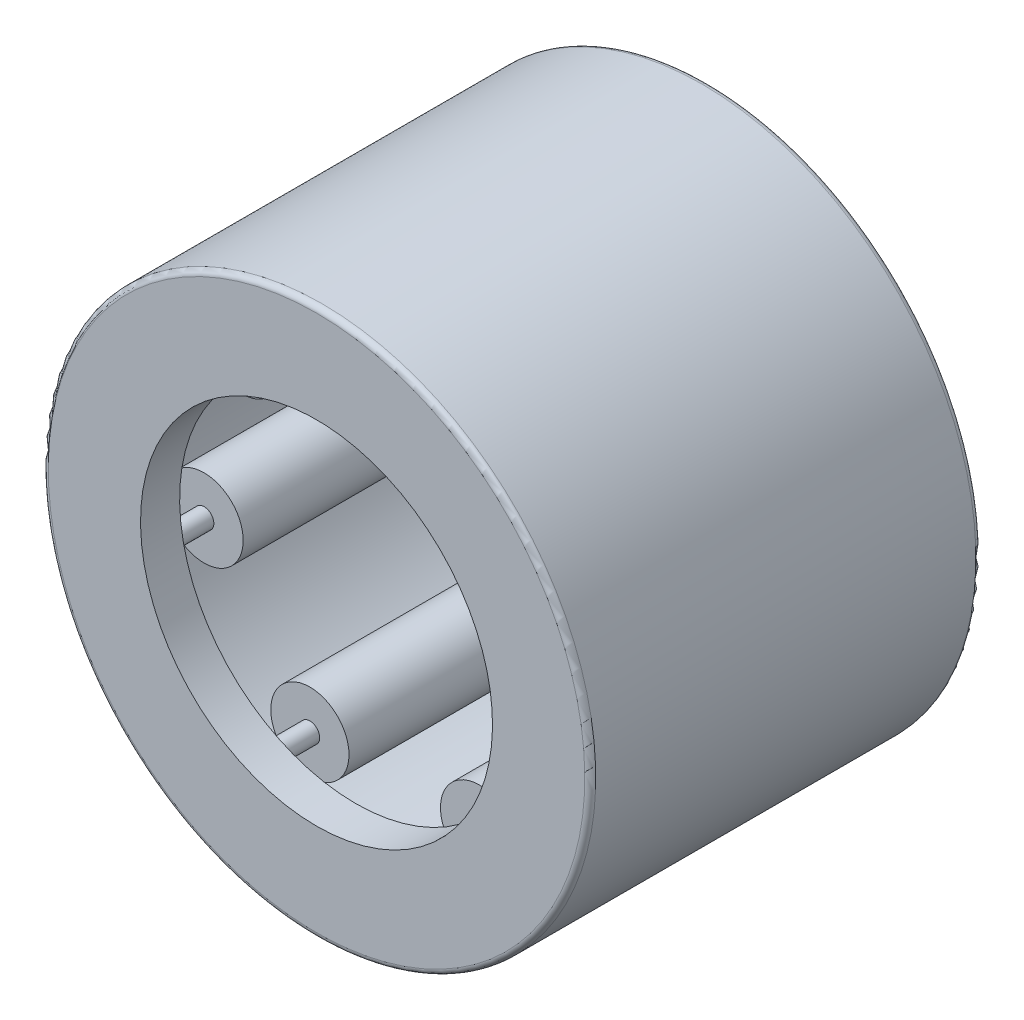
SolidWorks part; units mm, degrees
ref_plane "Front Plane" through (0, 0, 0) normal (0, 0, 1) x (1, 0, 0)
ref_plane "Top Plane" through (0, 0, 0) normal (0, 1, 0) x (1, 0, 0)
ref_plane "Right Plane" through (0, 0, 0) normal (1, 0, 0) x (0, 0, -1)
sketch "Sketch1" plane through (0, 0, 0) normal (1, 0, 0) x (0, 0, -1)
  line L0 (-3.9687, 0) -> (3.9688, 0) construction
  line L1 (0, 0) -> (0, 5.5563) construction
  line L2 (-3.9687, 0) -> (-3.9687, 5.5563) construction
  line L3 (-3.9687, 5.5563) -> (3.9687, 5.5563)
  line L4 (3.9687, 5.5563) -> (3.9688, 0) construction
  line L5 (3.9688, 0) -> (3.175, 0) construction
  line L6 (3.175, 0) -> (3.175, 4.7625) construction
  line L7 (3.175, 4.7625) -> (-3.175, 4.7625)
  line L8 (-3.175, 4.7625) -> (-3.175, 0) construction
  line L9 (-3.175, 0) -> (-3.9687, 0) construction
  line L10 (-3.9687, 5.5563) -> (-3.9687, 3.5719)
  line L11 (-3.9687, 3.5719) -> (-3.175, 3.5719)
  line L12 (-3.175, 3.5719) -> (-3.175, 4.7625)
  line L13 (3.175, 5.5563) -> (3.175, 4.7625) construction
  line L14 (3.175, 4.7625) -> (3.175, 3.5719)
  line L15 (3.175, 3.5719) -> (3.9687, 3.5719)
  line L16 (3.9687, 3.5719) -> (3.9687, 5.5563)
  line L17 (3.175, 4.7625) -> (3.175, 3.9688) construction
  line L18 (3.175, 3.9688) -> (3.175, 3.175) construction
  line L19 (3.175, -4.7625) -> (3.175, -3.9688) construction
  line L20 (3.175, -5.5563) -> (3.175, -4.7625) construction
  line L21 (3.9687, -3.5719) -> (3.9687, -5.5563) construction
  line L22 (3.175, -3.5719) -> (3.9687, -3.5719) construction
  line L23 (3.175, -4.7625) -> (3.175, -3.5719) construction
  line L24 (-3.175, -3.5719) -> (-3.175, -4.7625) construction
  line L25 (-3.9687, -3.5719) -> (-3.175, -3.5719) construction
  line L26 (-3.9687, -5.5563) -> (-3.9687, -3.5719) construction
  line L27 (3.175, -4.7625) -> (-3.175, -4.7625) construction
  line L28 (-3.9687, -5.5563) -> (3.9687, -5.5563) construction
  point P5 (0, 3.175)
  dimension "Width" = 7.9375
  dimension "OD" = 11.1125
  dimension "Shaft Dia" = 6.35
revolve "Revolve1" add sketch "Sketch1" angle 360 about L0
sketch "Sketch2" plane through (0, 0, 0) normal (1, 0, 0) x (0, 0, -1)
  line L0 (3.175, 4.7625) -> (-3.175, 4.7625) construction
  line L1 (-2.3813, 3.9688) -> (2.3813, 3.9688) construction
  line L2 (-2.3813, 3.9688) -> (-2.3813, 4.7625) construction
  line L3 (-2.3813, 4.7625) -> (2.3813, 4.7625)
  line L4 (2.3813, 3.9688) -> (2.3813, 4.7625) construction
  line L5 (3.175, 3.5719) -> (3.9687, 3.5719) construction
  line L6 (-3.175, 3.9688) -> (-2.3813, 3.9688) construction
  line L7 (2.3813, 3.9688) -> (3.175, 3.9688) construction
  line L8 (-3.9687, 3.5719) -> (-3.175, 3.5719) construction
  line L9 (-2.3813, 4.1672) -> (-2.3813, 3.7703) construction
  line L10 (-3.175, 3.9688) -> (-3.175, 3.5719) construction
  line L11 (-2.3813, 4.7625) -> (-2.3813, 4.1672)
  line L12 (2.3813, 4.7625) -> (2.3813, 4.1672)
  line L13 (2.3813, 4.1672) -> (-2.3813, 4.1672)
  line L14 (0, 4.7625) -> (0, 3.175) construction
  line L15 (-3.175, 3.5719) -> (-3.175, 4.7625) construction
  line L16 (-2.3813, 3.7703) -> (-3.175, 3.7703) construction
  line L17 (0, 0) -> (3.9687, 0) construction
  line L18 (-2.3813, -3.7703) -> (-3.175, -3.7703) construction
  line L19 (0, -4.7625) -> (0, -3.175) construction
  line L20 (-3.175, -3.9688) -> (-3.175, -3.5719) construction
  line L21 (-2.3813, -4.1672) -> (-2.3813, -3.7703) construction
  line L22 (2.3813, -3.9688) -> (3.175, -3.9688) construction
  line L23 (-3.175, -3.9688) -> (-2.3813, -3.9688) construction
  line L24 (2.3813, -3.9688) -> (2.3813, -4.7625) construction
  line L25 (-2.3813, -3.9688) -> (-2.3813, -4.7625) construction
  line L26 (-2.3813, -3.9688) -> (2.3813, -3.9688) construction
  line L27 (2.3813, -4.1672) -> (-2.3813, -4.1672) construction
  line L28 (2.3813, -4.7625) -> (2.3813, -4.1672) construction
  line L29 (-2.3813, -4.7625) -> (-2.3813, -4.1672) construction
  line L30 (-2.3813, -4.7625) -> (2.3813, -4.7625) construction
  line L31 (3.9687, -5.5562) -> (3.9687, 5.5563) construction
  point P16 (0, 3.9688)
revolve "Revolve2" add sketch "Sketch2" angle 360 about L1
sketch "Sketch3" plane through (0, 0, 0) normal (1, 0, 0) x (0, 0, -1)
  line L0 (3.175, 4.7625) -> (3.175, 3.5719) construction
  line L1 (-3.175, 3.9688) -> (3.175, 3.9688)
  line L2 (-3.175, 3.9688) -> (-3.175, 4.1672)
  line L3 (-3.175, 4.1672) -> (3.175, 4.1672)
  line L4 (3.175, 3.9688) -> (3.175, 4.1672)
  line L5 (0, 0) -> (3.9687, 0) construction
  line L6 (3.9687, -5.5562) -> (3.9687, 5.5563) construction
  line L7 (3.175, -3.9688) -> (3.175, -4.1672) construction
  line L8 (-3.175, -4.1672) -> (3.175, -4.1672) construction
  line L9 (-3.175, -3.9688) -> (-3.175, -4.1672) construction
  line L10 (-3.175, -3.9688) -> (3.175, -3.9688) construction
revolve "Revolve3" add sketch "Sketch3" angle 360 about L1
sketch "Sketch6" plane through (0, 0, 0) normal (0, 0, 1) x (1, 0, 0)
  line L0 (0, 0) -> (3.81, 1.1113) construction
  line L1 (0, 0) -> (0, 3.9688) construction
  line L2 (0, 3.9688) -> (3.81, 1.1113) construction
  circle A0 centre (0, 3.9688) radius 0.7937 construction
  circle A1 centre (0, 3.9688) radius 0.7937
  circle A2 centre (0, 0) radius 3.9688 construction
  circle A3 centre (3.81, 1.1113) radius 0.7937
  circle A4 centre (0, 0) radius 3.175 construction
  dimension "D1" = 1.5875
  dimension "D2" = 4.7625
ref_axis "Axis1" through (0, 0, -3.9688) along (0, 0, 1)
pattern_circular "CirPattern1" count 7 every 51.429 about axis through (0, 0, -3.9688) along (0, 0, 1) of bodies 166 167
fillet "Fillet1" radius 0.1111 2 edges at (0, -5.5562, -3.9687) (0, -5.5562, 3.9687)
sketch "Sketch4" plane through (0, 0, 0) normal (1, 0, 0) x (0, 0, -1)
  line L1 (3.8576, 3.175) -> (2.3813, 3.175)
  line L2 (3.8576, 3.175) -> (3.8576, 3.5719)
  line L3 (3.8576, 3.5719) -> (2.3813, 3.5719)
  line L4 (2.3813, 3.175) -> (2.3813, 3.5719)
  line L5 (-3.9687, 3.5719) -> (-3.175, 3.5719) construction
  line L6 (3.8576, -5.5562) -> (3.8576, 5.5563) construction
  line L7 (2.3813, 4.7625) -> (2.3813, 4.1672) construction
revolve "Revolve4" [suppressed] add sketch "Sketch4" angle 360 about L0
sketch "Sketch5" plane through (0, 0, 0) normal (1, 0, 0) x (0, 0, -1)
  line L0 (-3.8576, 5.5563) -> (-3.8576, -5.5562) construction
  line L1 (-2.3813, 3.175) -> (-3.8576, 3.175)
  line L2 (-2.3813, 3.175) -> (-2.3813, 3.5719)
  line L3 (-2.3813, 3.5719) -> (-3.8576, 3.5719)
  line L4 (-3.8576, 3.175) -> (-3.8576, 3.5719)
  line L6 (-2.3813, 4.7625) -> (-2.3813, 4.1672) construction
  line L7 (-3.9687, 3.5719) -> (-3.175, 3.5719) construction
revolve "Revolve5" [suppressed] add sketch "Sketch5" angle 360 about L0
equation "\"Rollers@CirPattern1\" = \"OD@Sketch1\"*16"
equation "\"D1@Fillet1\" = \"OD@Sketch1\"*.01"
equation "\"Angle@CirPattern1\"= 360 / \"Rollers@CirPattern1\""
